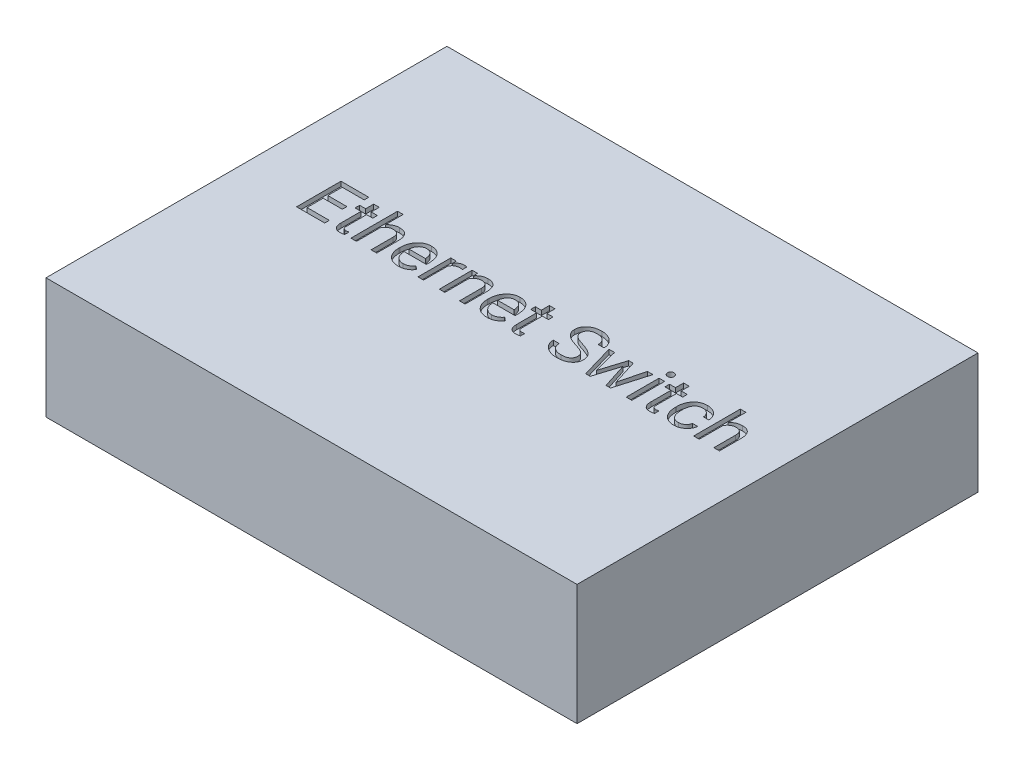
SolidWorks part; units mm, degrees
ref_plane "Front Plane" through (0, 0, 0) normal (0, 0, 1) x (1, 0, 0)
ref_plane "Top Plane" through (0, 0, 0) normal (0, 1, 0) x (1, 0, 0)
ref_plane "Right Plane" through (0, 0, 0) normal (1, 0, 0) x (0, 0, -1)
sketch "Sketch1" plane through (0, 0, 0) normal (0, 1, 0) x (1, 0, 0)
  line L1 (0, 0) -> (114.046, 0)
  line L2 (0, 0) -> (0, 86.106)
  line L3 (0, 86.106) -> (114.046, 86.106)
  line L4 (114.046, 0) -> (114.046, 86.106)
  dimension "D1" = 86.106
  dimension "D2" = 114.046
extrude "Boss-Extrude1" add sketch "Sketch1" along normal mid plane 25.908
sketch "Sketch2" plane through (0, 12.954, 0) normal (0, 1, 0) x (1, 0, 0)
  text T0 "Ethernet Switch" font "Roboto" height 9.525
  point P1 (15.3782, 30.1235)
  point P2 (18.3162, 39.9655)
extrude "Cut-Extrude1" cut sketch "Sketch2" against normal blind 1
